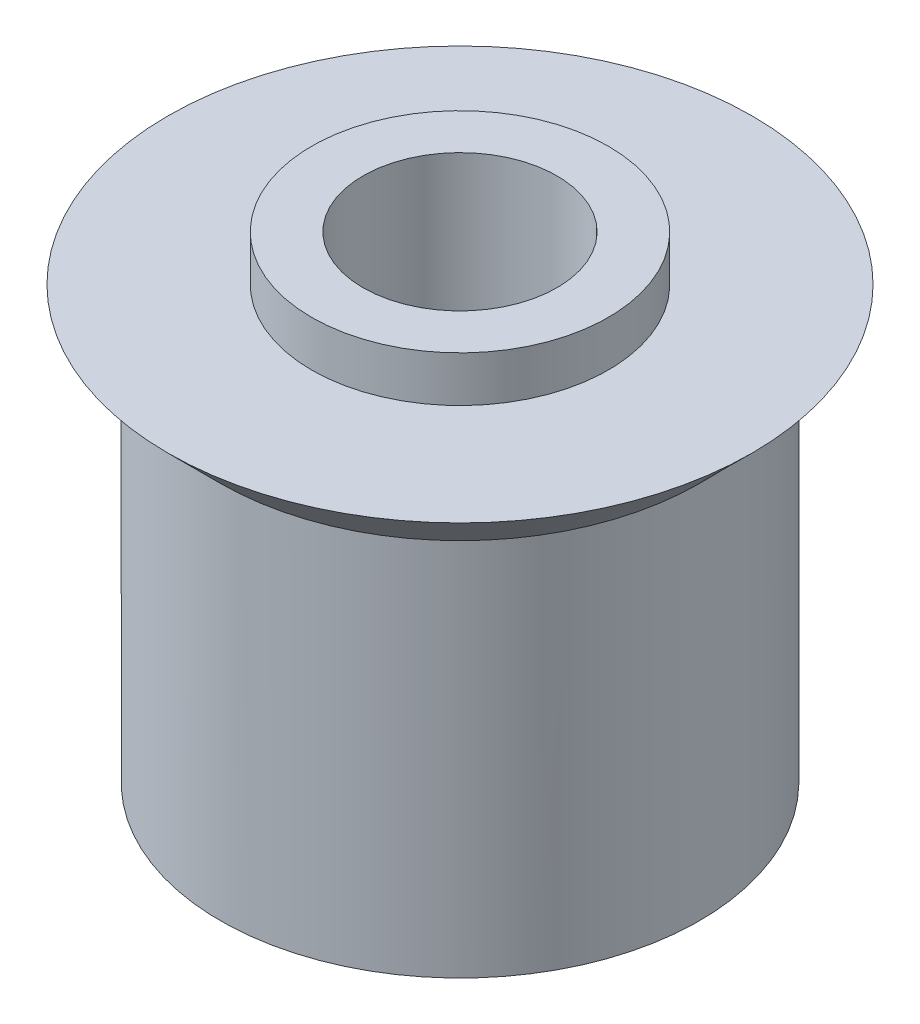
SolidWorks part; units mm, degrees
ref_plane "前视基准面" through (0, 0, 0) normal (0, 0, 1) x (1, 0, 0)
ref_plane "上视基准面" through (0, 0, 0) normal (0, 1, 0) x (1, 0, 0)
ref_plane "右视基准面" through (0, 0, 0) normal (1, 0, 0) x (0, 0, -1)
sketch "草图1" plane through (0, 0, 0) normal (0, 1, 0) x (1, 0, 0)
  circle A0 centre (0, 0) radius 9.4
  dimension "D1" = 18.8
extrude "凸台-拉伸1" add sketch "草图1" along normal blind 15.5
sketch "草图2" plane through (0, 0, 0) normal (0, 0, 1) x (1, 0, 0)
  line L0 (0, 18.9) -> (12.8, 18.9)
  line L1 (9.4, 15.5) -> (-9.4, 15.5) construction
  line L2 (9.4, 15.5) -> (0, 15.5)
  line L3 (9.4, 15.5) -> (12.8, 18.9)
  line L4 (0, 15.5) -> (0, 18.9)
  dimension "D1" = 135
  dimension "D2" = 3.4
revolve "旋转1" add sketch "草图2" angle 360 about L4
sketch "草图3" plane through (0, 18.9, 0) normal (0, 1, 0) x (1, 0, 0)
  circle A0 centre (0, 0) radius 6.5
extrude "凸台-拉伸2" add sketch "草图3" along normal blind 2
sketch "草图4" plane through (0, 20.9, 0) normal (0, 1, 0) x (1, 0, 0)
  circle A0 centre (0, 0) radius 4.25
sketch "草图5" plane through (0, 0, 0) normal (0, -1, 0) x (1, 0, 0)
  circle A0 centre (0, 0) radius 10.5
extrude "凸台-拉伸4" add sketch "草图5" against normal blind 17
extrude "切除-拉伸1" cut sketch "草图4" against normal blind 31
